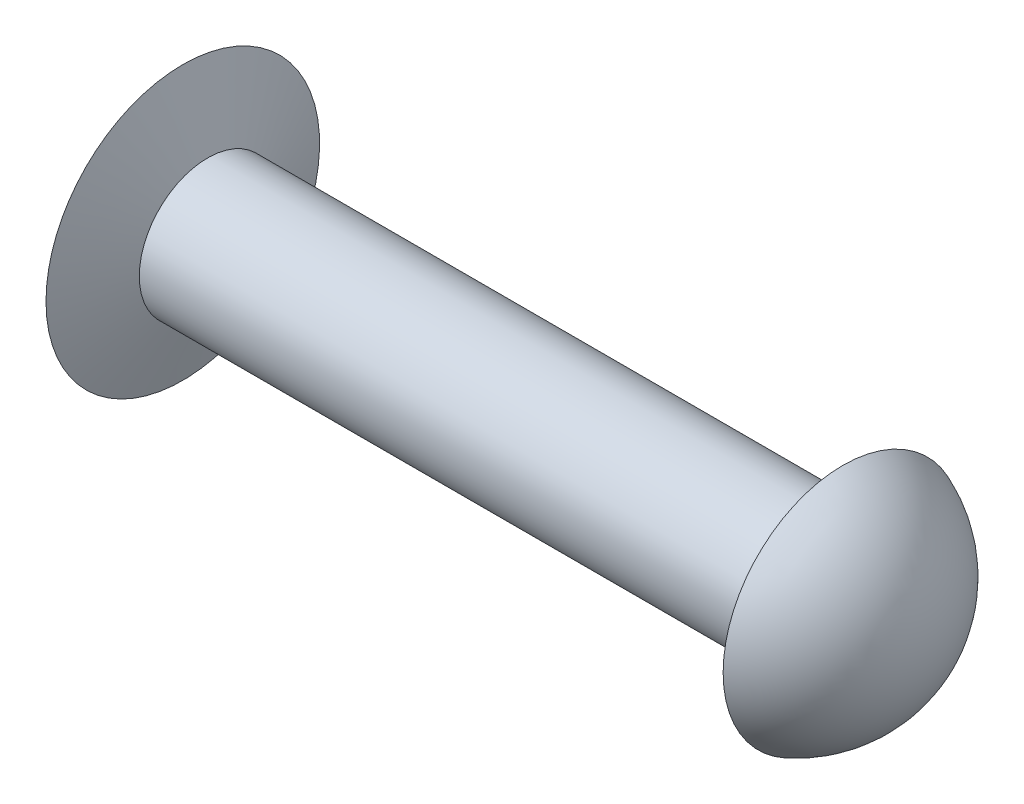
SolidWorks part; units mm, degrees
ref_plane "Plane1" through (0, 0, 0) normal (0, 0, 1) x (1, 0, 0)
ref_plane "Plane2" through (0, 0, 0) normal (0, 1, 0) x (1, 0, 0)
ref_plane "Plane3" through (0, 0, 0) normal (1, 0, 0) x (0, 0, -1)
sketch "Sketch1" plane through (0, 0, 0) normal (0, 0, 1) x (1, 0, 0)
  line L0 (-39, 0) -> (6, 0) construction
  line L1 (-30.9508, 0) -> (0, 0)
  line L2 (-27.8589, 3) -> (-28.9508, 6)
  line L3 (-27.8589, 3) -> (0, 3)
  line L4 (0, 3) -> (0, 0)
  line L5 (-27.8589, -3) -> (-28.9508, -6) construction
  arc A0 (-28.9508, 6) -> (-30.9508, 0) centre (-20.9508, 0) ccw
  point P12 (-27.8589, 3)
  dimension "HeadRadius" = 10
  dimension "Diameter" = 6
  dimension "D1" = 140
  dimension "GripLength" = 28.9508
  dimension "HeadDia" = 12
revolve "Base-Revolve" add sketch "Sketch1" angle 360 about L0
sketch "Sketch2" plane through (0, 0, 0) normal (0, 0, 1) x (1, 0, 0)
  line L0 (-49, 0) -> (29, 0) construction
  line L1 (0, 0) -> (3.6, 0)
  line L2 (0, 0) -> (0, 5.25)
  arc A0 (3.6, 0) -> (0, 5.25) centre (-2.0281, 0) ccw
  dimension "HeadDiaA" = 10.5
  dimension "HeadHtA" = 3.6
revolve "HeadTypeA" add sketch "Sketch2" angle 360 about L0
sketch "Sketch3" plane through (0, 0, 0) normal (0, 0, 1) x (1, 0, 0)
  line L0 (30, 0) -> (-54, 0) construction
  line L1 (-39, 0) -> (6, 0) construction
  line L2 (0, 0) -> (0, 5.25)
  line L3 (0, 5.25) -> (-2.9323, 3)
  line L4 (-2.9323, 0) -> (0, 0)
  line L5 (0, -5.25) -> (-2.9323, -3) construction
  line L6 (-2.9323, 0) -> (-2.9323, 3)
  dimension "HeadDiaB" = 10.5
  dimension "D3" = 6
  dimension "D2" = 75
revolve "HeadTypeB" [suppressed] add sketch "Sketch3" angle 360 about L0
equation "\"D3@Sketch3\" = \"Diameter@Sketch1\""
